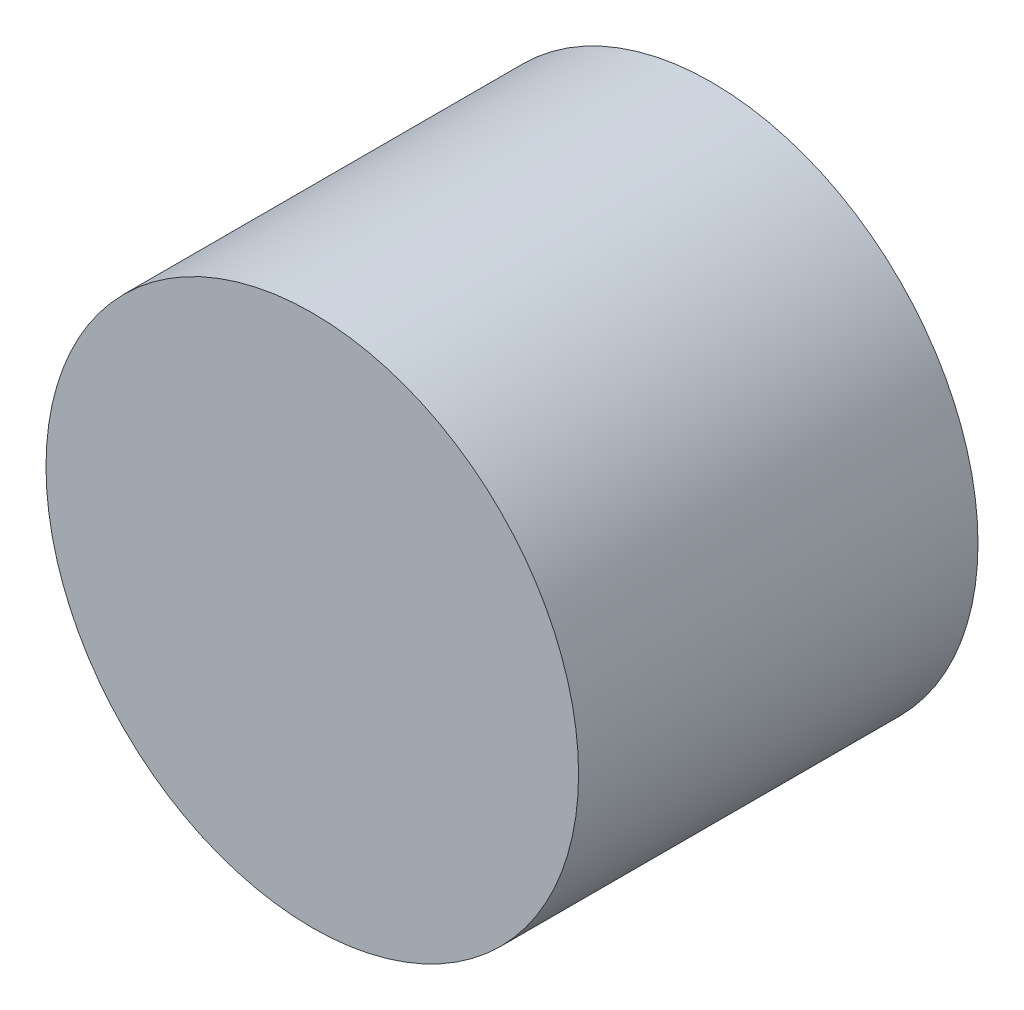
SolidWorks part; units mm, degrees
material "Parachute"
ref_plane "Front Plane" through (0, 0, 0) normal (0, 0, 1) x (1, 0, 0)
ref_plane "Top Plane" through (0, 0, 0) normal (0, 1, 0) x (1, 0, 0)
ref_plane "Right Plane" through (0, 0, 0) normal (1, 0, 0) x (0, 0, -1)
sketch "Sketch1" plane through (0, 0, 0) normal (0, 0, 1) x (1, 0, 0)
  circle A0 centre (0, 0) radius 50.8
  dimension "D1" = 101.6
extrude "Extrude1" add sketch "Sketch1" along normal blind 76.2
